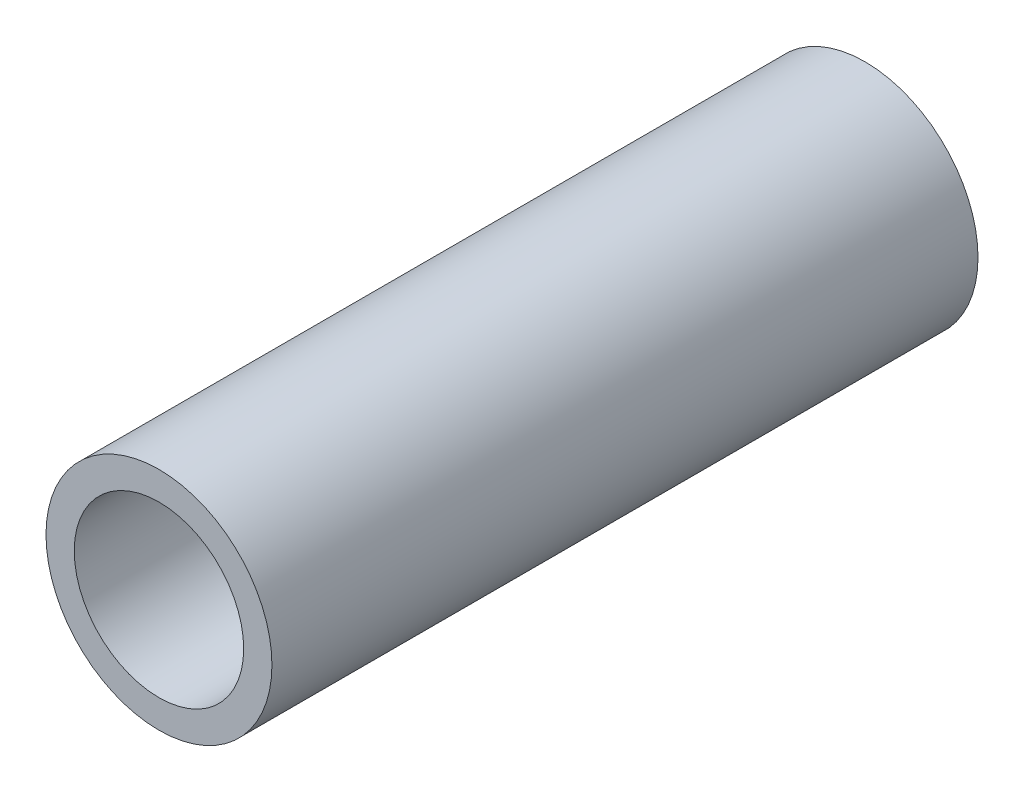
SolidWorks part; units mm, degrees
ref_plane "Front Plane" through (0, 0, 0) normal (0, 0, 1) x (1, 0, 0)
ref_plane "Top Plane" through (0, 0, 0) normal (0, 1, 0) x (1, 0, 0)
ref_plane "Right Plane" through (0, 0, 0) normal (1, 0, 0) x (0, 0, -1)
sketch "Sketch1" plane through (0, 0, 0) normal (0, 0, 1) x (1, 0, 0)
  circle A0 centre (0, 0) radius 3
  circle A1 centre (0, 0) radius 4
  dimension "D1" = 8
  dimension "D2" = 6
extrude "Boss-Extrude1" add sketch "Sketch1" along normal blind 25
